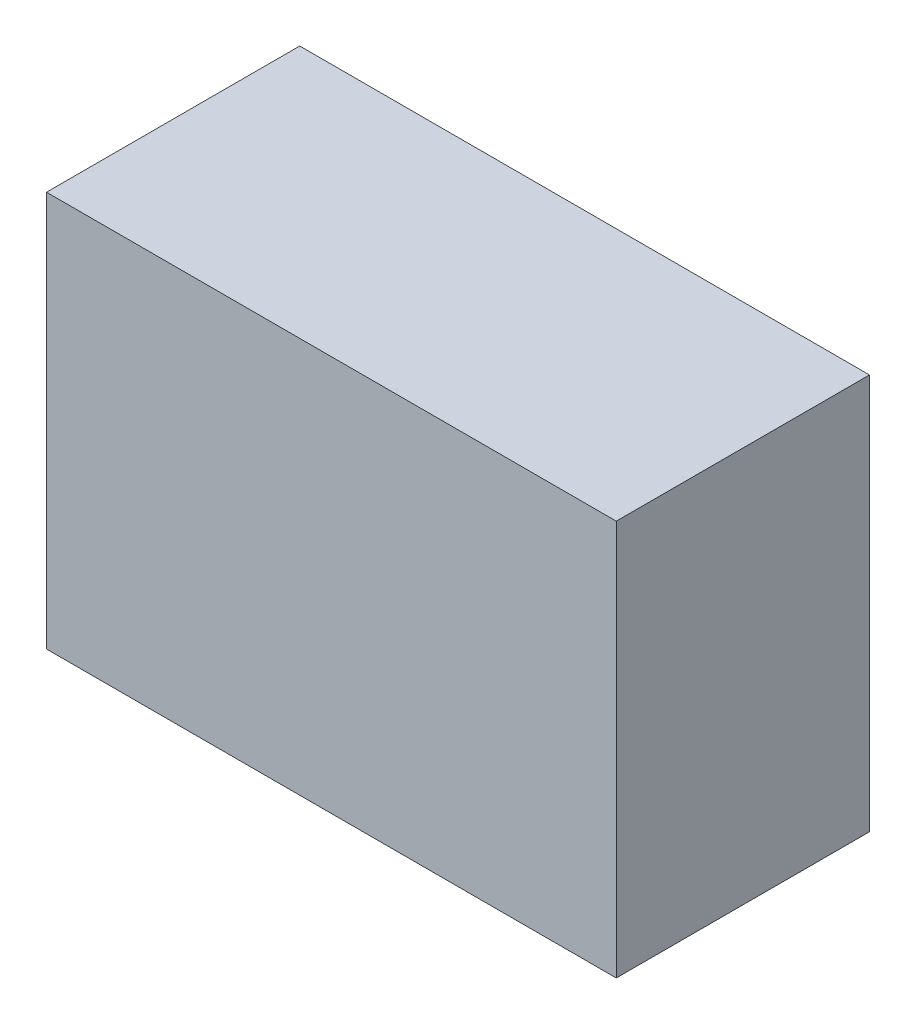
SolidWorks part; units mm, degrees
ref_plane "Front Plane" through (0, 0, 0) normal (0, 0, 1) x (1, 0, 0)
ref_plane "Top Plane" through (0, 0, 0) normal (0, 1, 0) x (1, 0, 0)
ref_plane "Right Plane" through (0, 0, 0) normal (1, 0, 0) x (0, 0, -1)
sketch "Sketch1" plane through (0, 0, 0) normal (0, 0, 1) x (1, 0, 0)
  line L1 (-405.9713, -309.7305) -> (-863.1713, -309.7305)
  line L2 (-405.9713, -309.7305) -> (-405.9713, 7.7695)
  line L3 (-405.9713, 7.7695) -> (-863.1713, 7.7695)
  line L4 (-863.1713, -309.7305) -> (-863.1713, 7.7695)
  point P4 (-634.5713, 7.7695)
  dimension "D1" = 457.2
  dimension "D2" = 317.5
extrude "Boss-Extrude1" add sketch "Sketch1" along normal blind 203.2
